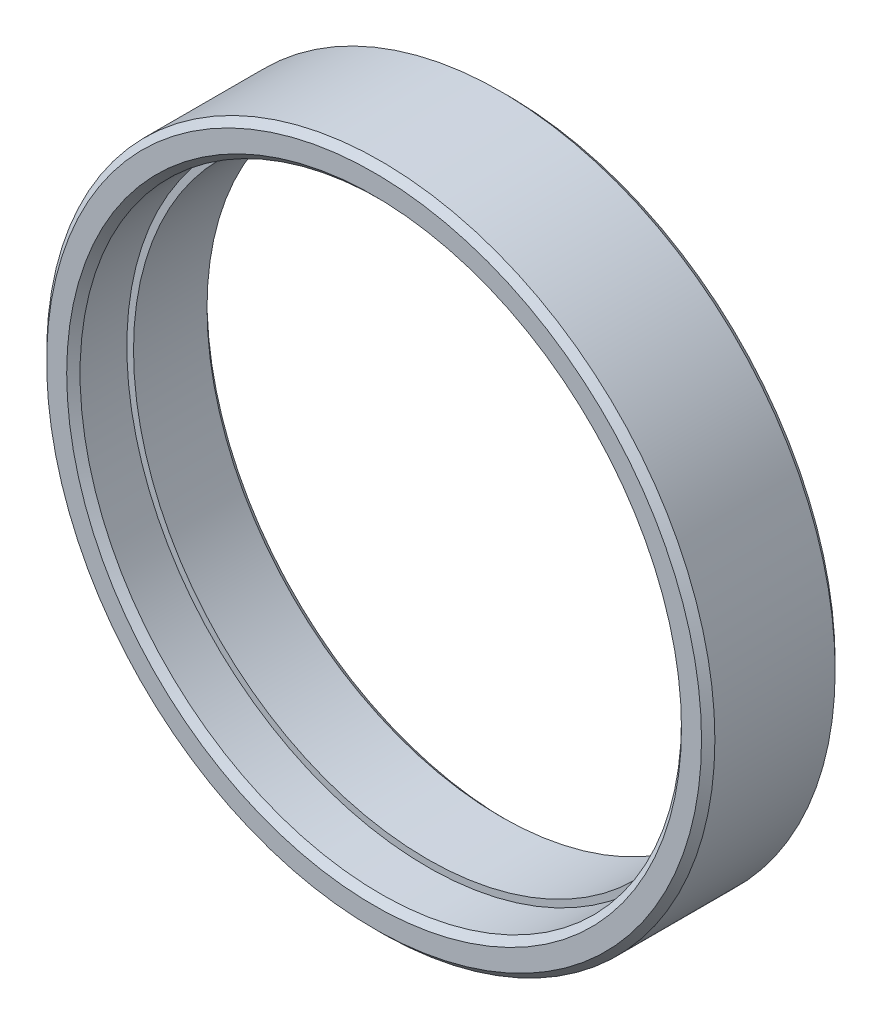
SolidWorks part; units mm, degrees
ref_plane "정면" through (0, 0, 0) normal (0, 0, 1) x (1, 0, 0)
ref_plane "윗면" through (0, 0, 0) normal (0, 1, 0) x (1, 0, 0)
ref_plane "우측면" through (0, 0, 0) normal (1, 0, 0) x (0, 0, -1)
sketch "스케치1" plane through (0, 0, 0) normal (0, 0, 1) x (1, 0, 0)
  circle A0 centre (0, 0) radius 44
  circle A1 centre (0, 0) radius 50
  dimension "D1" = 100
  dimension "D2" = 88
extrude "보스-돌출1" add sketch "스케치1" along normal mid plane 20
sketch "스케치2" plane through (0, 0, 10) normal (0, 0, 1) x (1, 0, 0)
  circle A0 centre (0, 0) radius 45
  dimension "D1" = 90
extrude "컷-돌출1" cut sketch "스케치2" against normal blind 8
chamfer "모따기1" distance 1 angle 45 4 edges at (45, 0, 10) (50, 0, 10) (44, 0, -10) (50, 0, -10)
